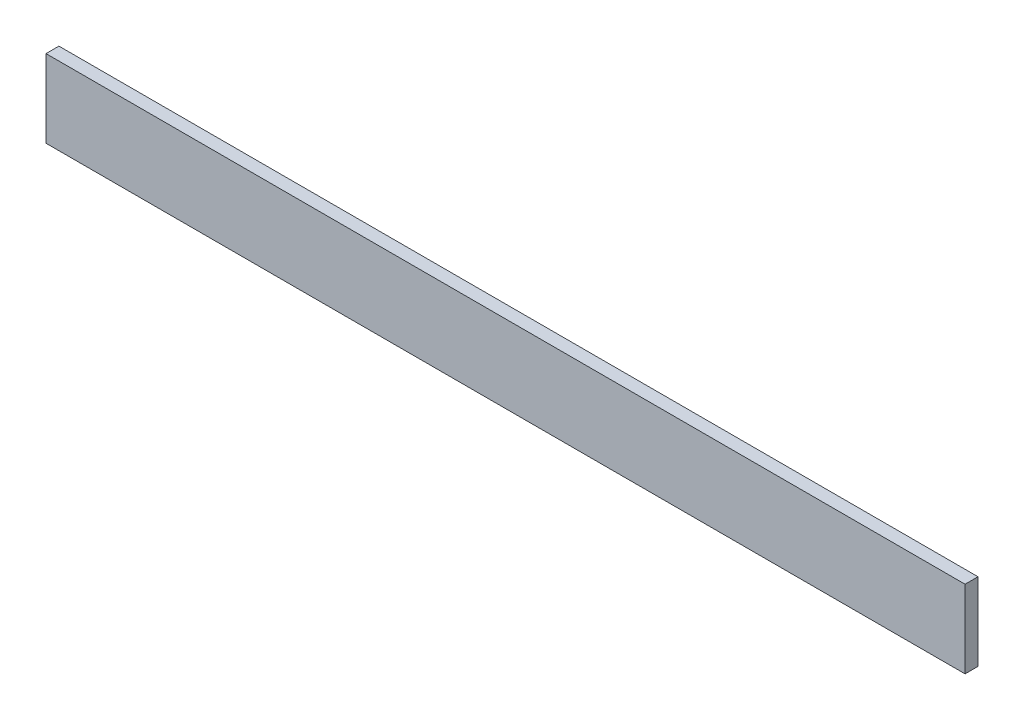
SolidWorks part; units mm, degrees
ref_plane "Front Plane" through (0, 0, 0) normal (0, 0, 1) x (1, 0, 0)
ref_plane "Top Plane" through (0, 0, 0) normal (0, 1, 0) x (1, 0, 0)
ref_plane "Right Plane" through (0, 0, 0) normal (1, 0, 0) x (0, 0, -1)
sketch "Sketch1" plane through (0, 0, 0) normal (1, 0, 0) x (0, 0, -1)
  line L1 (0, 0) -> (50.8, 0)
  line L2 (0, 0) -> (0, 304.8)
  line L3 (0, 304.8) -> (50.8, 304.8)
  line L4 (50.8, 0) -> (50.8, 304.8)
extrude "Boss-Extrude1" add sketch "Sketch1" along normal blind 3606.8
